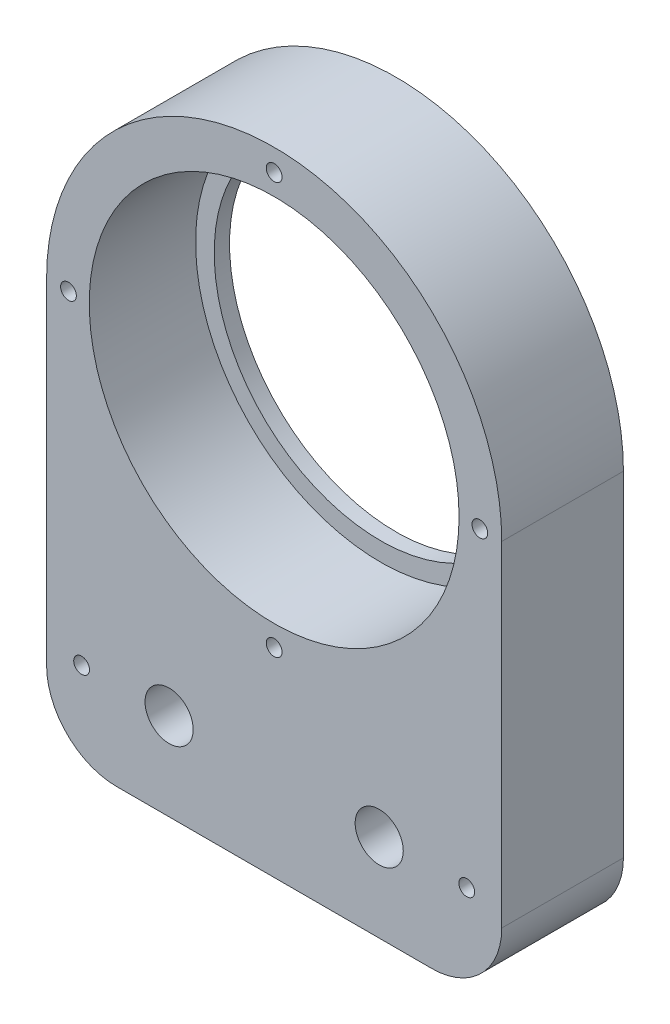
SolidWorks part; units mm, degrees
ref_plane "Спереди" through (0, 0, 0) normal (0, 0, 1) x (1, 0, 0)
ref_plane "Сверху" through (0, 0, 0) normal (0, 1, 0) x (1, 0, 0)
ref_plane "Справа" through (0, 0, 0) normal (1, 0, 0) x (0, 0, -1)
sketch "Эскиз2" plane through (0, 0, 0) normal (0, 0, 1) x (1, 0, 0)
  line L0 (0, 0) -> (0, 0.25)
  line L1 (-26, -10) -> (26, -10) construction
  line L2 (-26, 26.25) -> (26, 26.25)
  line L3 (-26, 26.25) -> (-26, -20)
  line L4 (-26, -20) -> (26, -20)
  line L5 (26, 26.25) -> (26, -20)
  line L6 (0, 26.25) -> (0, -20) construction
  circle A0 centre (0, 26.25) radius 26
  circle A1 centre (0, 26.25) radius 19
  circle A2 centre (-12, -10) radius 2.75
  circle A3 centre (12, -10) radius 2.75
  dimension "D1" = 52
  dimension "D4" = 38
  dimension "D6" = 5.5
  dimension "D2" = 0.25
  dimension "D3" = 20
  dimension "D5" = 10
  dimension "D7" = 24
extrude "Бобышка-Вытянуть1" add sketch "Эскиз2" along normal blind 13.9
sketch "Эскиз3" plane through (0, 0, 13.9) normal (0, 0, 1) x (1, 0, 0)
  circle A0 centre (0, 26.25) radius 21.125
  dimension "D1" = 42.25
extrude "Вырез-Вытянуть1" cut sketch "Эскиз3" against normal blind 12.15
sketch "Эскиз4" plane through (0, 0, 0) normal (0, 0, -1) x (-1, 0, 0)
  circle A0 centre (-12, -10) radius 5
  circle A1 centre (12, -10) radius 5
  dimension "D1" = 10
  dimension "D2" = 10
extrude "Вырез-Вытянуть2" cut sketch "Эскиз4" against normal blind 3
fillet "Скругление1" radius 8 2 edges at (-26, -20, 6.95) (26, -20, 6.95)
sketch "Эскиз5" plane through (0, 0, 13.9) normal (0, 0, 1) x (1, 0, 0)
  line L1 (-18, -20) -> (18, -20) construction
  line L2 (0, 26.25) -> (0, -20) construction
  circle A2 centre (0, 26.25) radius 23.5 construction
  circle A3 centre (0, 26.25) radius 21.125 construction
  circle A4 centre (0, 49.75) radius 0.9
  circle A5 centre (-23.5, 26.25) radius 0.9
  circle A6 centre (0, 2.75) radius 0.9
  circle A7 centre (23.5, 26.25) radius 0.9
  circle A8 centre (-22, -10) radius 0.9
  circle A9 centre (22, -10) radius 0.9
  dimension "D1" = 47
  dimension "D2" = 1.8
  dimension "D6" = 1.8
  dimension "D4" = 10
  dimension "D5" = 44
  dimension "D3" = 4
extrude "Вырез-Вытянуть3" cut sketch "Эскиз5" against normal through all
equation "\"big_bearing_d1\"= 19.9"
equation "\"big_bearing_d2\"= 42"
equation "\"big_bearing_h\"= 11.9"
equation "\"print_offset\"= 0.5"
equation "\"small_bearing_d1\"= 2.9"
equation "\"small_bearing_d2\"= 10"
equation "\"small_bearing_h\"= 4"
equation "\"tube_d\"= 16"
equation "\"small_bearing_distance\"= 2"
equation "\"D1@Эскиз2\"=\"big_bearing_d2\"+5*2"
equation "\"D2@Эскиз2\"=\"print_offset\"/2"
equation "\"D4@Эскиз2\"=\"big_bearing_d2\"-4"
equation "\"D1@Бобышка-Вытянуть1\"=\"big_bearing_h\"+2"
equation "\"D1@Эскиз3\"=\"big_bearing_d2\"+\"print_offset\"/2"
equation "\"D1@Вырез-Вытянуть1\"=\"big_bearing_h\"+\"print_offset\"/2"
equation "\"D2@Эскиз4\"=\"D1@Эскиз4\""
equation "\"D6@Эскиз5\"=\"D2@Эскиз5\""
